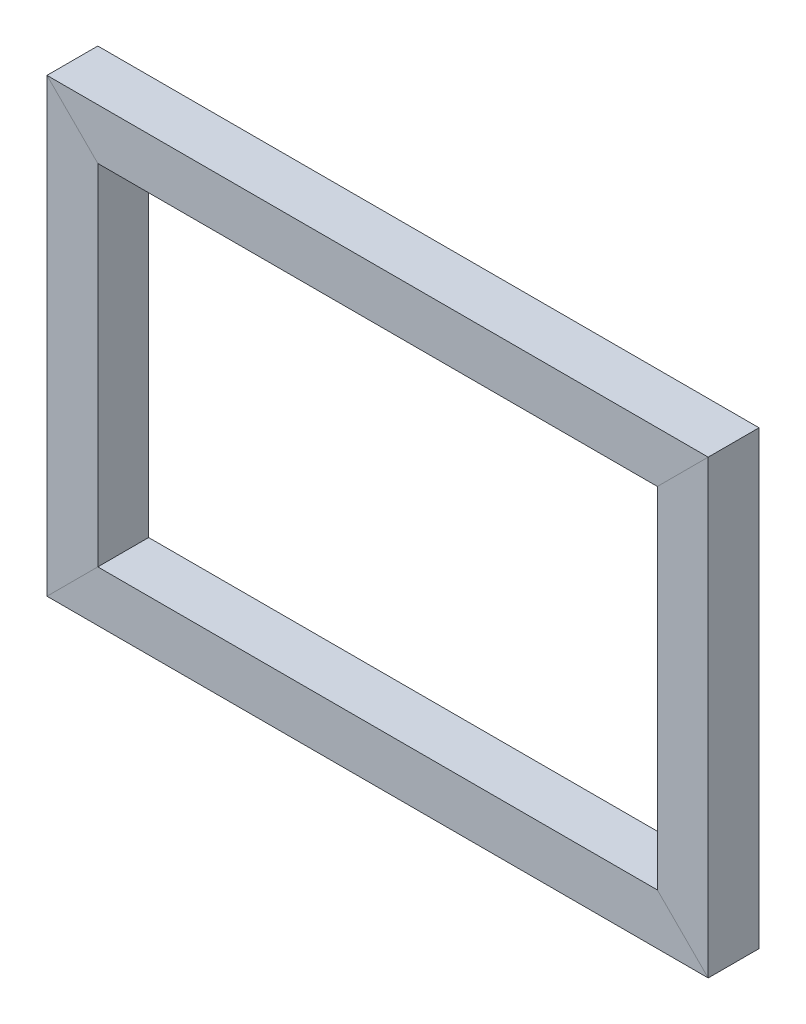
SolidWorks part; units mm, degrees
ref_plane "Alzado" through (0, 0, 0) normal (0, 0, 1) x (1, 0, 0)
ref_plane "Planta" through (0, 0, 0) normal (0, 1, 0) x (1, 0, 0)
ref_plane "Vista lateral" through (0, 0, 0) normal (1, 0, 0) x (0, 0, -1)
sketch "Croquis1" plane through (0, 0, 0) normal (0, 0, 1) x (1, 0, 0)
  line L1 (0, 0) -> (610, 0)
  line L2 (0, 0) -> (0, 400)
  line L3 (0, 400) -> (610, 400)
  line L4 (610, 0) -> (610, 400)
  dimension "D1" = 400
  dimension "D2" = 610
other "Al tube (square) 2 SQ X .049 WALL(1)"
ref_plane "Plano1" through (0, 0, 0) normal (0, 1, 0) x (-1, 0, 0)
sketch "Sketch1" plane through (0, 0, 0) normal (0, 1, 0) x (-1, 0, 0)
  line L0 (-24.1554, -24.1554) -> (-24.1554, 24.1554)
  line L1 (24.1554, 24.1554) -> (-24.1554, 24.1554)
  line L2 (24.1554, 24.1554) -> (24.1554, -24.1554)
  line L3 (-24.1554, -24.1554) -> (24.1554, -24.1554)
  line L4 (-25.4, -25.4) -> (25.4, -25.4)
  line L5 (-25.4, -25.4) -> (-25.4, 25.4)
  line L6 (25.4, 25.4) -> (-25.4, 25.4)
  line L7 (25.4, 25.4) -> (25.4, -25.4)
  line L8 (0, -24.1554) -> (0, -25.4) construction
  line L9 (0, -24.1554) -> (0, 24.1554) construction
  line L10 (0, 24.1554) -> (0, 25.4) construction
  line L11 (25.4, 0) -> (24.1554, 0) construction
  line L12 (24.1554, 0) -> (-24.1554, 0) construction
  line L13 (-24.1554, 0) -> (-25.4, 0) construction
  point P14 (0, 0)
  dimension "Thickness" = 1.2446
  dimension "V_leg" = 50.8
  dimension "H_leg" = 50.8
